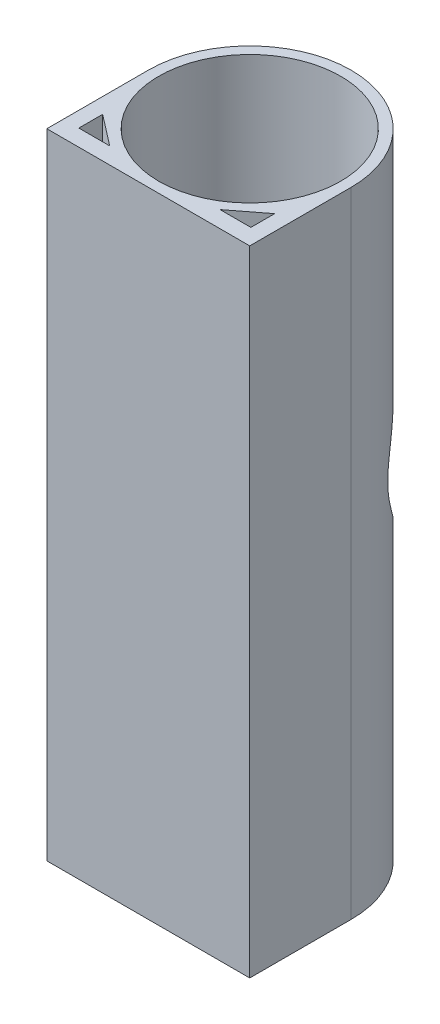
SolidWorks part; units mm, degrees
ref_plane "Front Plane" through (0, 0, 0) normal (0, 0, 1) x (1, 0, 0)
ref_plane "Top Plane" through (0, 0, 0) normal (0, 1, 0) x (1, 0, 0)
ref_plane "Right Plane" through (0, 0, 0) normal (1, 0, 0) x (0, 0, -1)
sketch "Sketch1" plane through (0, 0, 0) normal (0, 1, 0) x (1, 0, 0)
  line L0 (16, -16) -> (-16, -16)
  line L1 (-16, -16) -> (-16, 0)
  line L2 (0, -55) -> (0, 55) construction
  line L3 (16, -16) -> (16, 0)
  line L4 (-13.567, -13.3875) -> (-8.7, -13.3875)
  line L5 (-8.7, -13.3875) -> (-13.567, -9.6312)
  line L6 (-13.567, -9.6312) -> (-13.567, -13.3875)
  line L7 (13.567, -13.3875) -> (8.7, -13.3875)
  line L8 (8.7, -13.3875) -> (13.567, -9.6312)
  line L9 (13.567, -9.6312) -> (13.567, -13.3875)
  arc A0 (16, 0) -> (-16, 0) centre (0, 0) ccw
  circle A1 centre (0, 0) radius 14.35
  point P10 (0, -16)
  dimension "D1" = 32
  dimension "D2" = 1.65
extrude "Boss-Extrude1" add sketch "Sketch1" along normal blind 100
sketch "Sketch2" plane through (0, 0, 16) normal (0, 0, 1) x (1, 0, 0)
  line L0 (0, -55) -> (0, 55) construction
  circle A0 centre (0, 54.8666) radius 13.97
  dimension "D1" = 27.94
extrude "Cut-Extrude3" cut sketch "Sketch2" against normal mid plane 30 from offset 35
